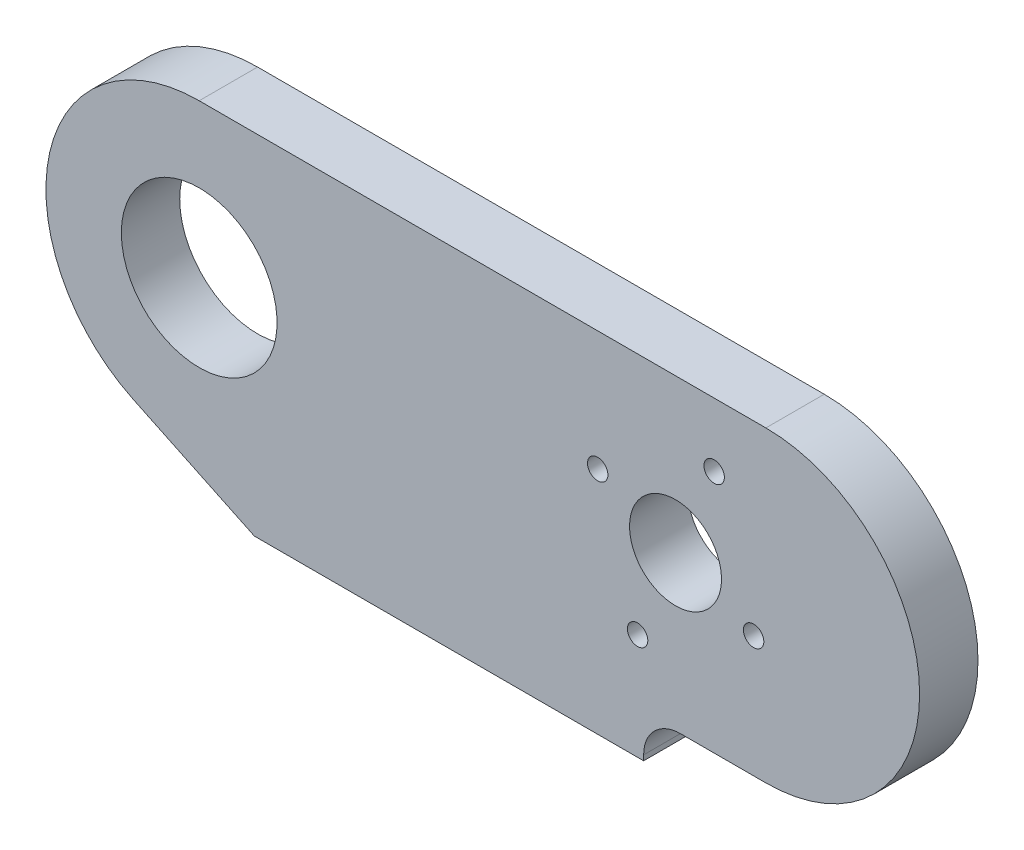
SolidWorks part; units mm, degrees
material "6061-T6 (SS)"
ref_plane "Front Plane" through (0, 0, 0) normal (0, 0, 1) x (1, 0, 0)
ref_plane "Top Plane" through (0, 0, 0) normal (0, 1, 0) x (1, 0, 0)
ref_plane "Right Plane" through (0, 0, 0) normal (1, 0, 0) x (0, 0, -1)
sketch "Sketch1" plane through (0, 0, 0) normal (0, 0, 1) x (1, 0, 0)
  line L0 (0, 0) -> (9, 0) construction
  line L1 (9, 0) -> (9, -32) construction
  line L2 (9, -32) -> (72.5, -32)
  line L3 (72.5, -32) -> (72.5, -25.1543)
  line L5 (9, -32) -> (-10.7712, -22.5606)
  line L6 (77.7, 25) -> (0, 25)
  line L7 (0, 0) -> (77.7, 0) construction
  line L8 (72.5, -25.1543) -> (79.6656, -25.1543)
  line L9 (77.7, 25) -> (92.4403, 25)
  line L11 (92.4403, -25.1543) -> (79.6656, -25.1543)
  circle A0 centre (0, 0) radius 12.7
  arc A1 (0, 25) -> (-10.7712, -22.5606) centre (0, 0) ccw
  circle A3 centre (77.7, 0) radius 7.5
  arc A4 (92.4403, 25) -> (92.4403, -25.1543) centre (92.4403, -0.0772) cw
  dimension "D1" = 25.4
  dimension "D4" = 50
  dimension "D7" = 77.7
  dimension "D6" = 15
  dimension "D2" = 9
  dimension "D3" = 32
  dimension "D5" = 63.5
  dimension "D8" = 14.7403
extrude "Boss-Extrude1" add sketch "Sketch1" along normal blind 9.525
fillet "Fillet1" radius 6 1 edges at (72.5, -25.1543, 4.7625)
ref_plane "Plane1" through (0, -32, 0) normal (0, 1, 0) x (1, 0, 0)
sketch "Sketch3" plane through (0, 0, 0) normal (0, 0, -1) x (-1, 0, 0)
  circle A0 centre (-77.6825, 0) radius 24.6751
sketch "Sketch4" plane through (0, 0, 0) normal (0, 0, -1) x (-1, 0, 0)
  circle A0 centre (-77.7, 0) radius 24.4293
sketch "Sketch5" plane through (0, 0, 0) normal (0, 0, -1) x (-1, 0, 0)
  circle A0 centre (-77.7, 0) radius 22.6348
sketch "Sketch6" plane through (0, 0, 9.525) normal (0, 0, 1) x (1, 0, 0)
  circle A0 centre (71.5133, -14.6732) radius 1.665 construction
  circle A1 centre (65.0067, 5.474) radius 1.665 construction
  circle A2 centre (84.0038, 14.6233) radius 1.665 construction
  circle A3 centre (90.4382, -5.3686) radius 1.665 construction
  circle A4 centre (71.5133, -14.6732) radius 1.665
  circle A5 centre (65.0067, 5.474) radius 1.665
  circle A6 centre (84.0038, 14.6233) radius 1.665
  circle A7 centre (90.4382, -5.3686) radius 1.665
extrude "Cut-Extrude1" cut sketch "Sketch6" against normal through all
